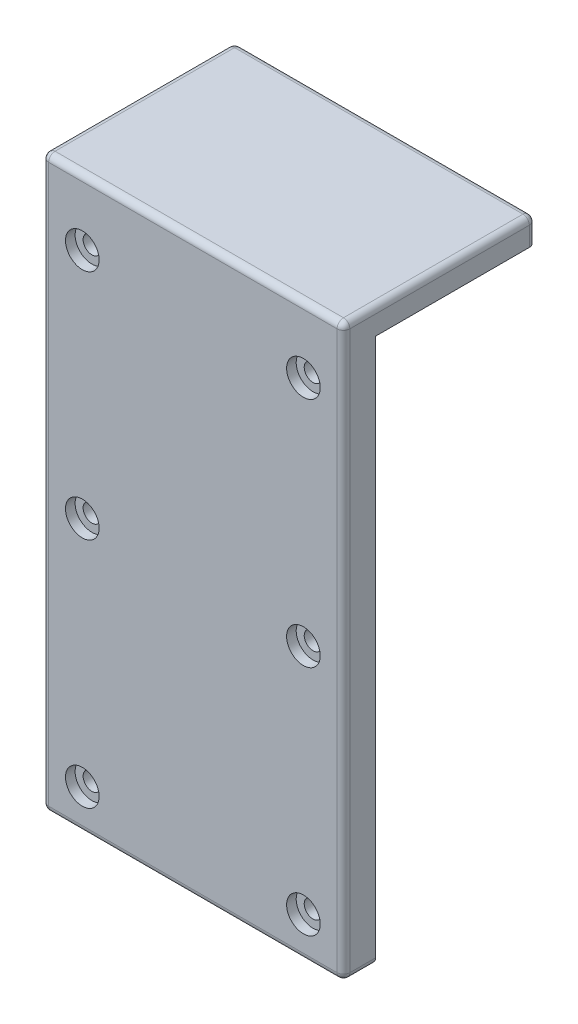
SolidWorks part; units mm, degrees
ref_plane "Front Plane" through (0, 0, 0) normal (0, 0, 1) x (1, 0, 0)
ref_plane "Top Plane" through (0, 0, 0) normal (0, 1, 0) x (1, 0, 0)
ref_plane "Right Plane" through (0, 0, 0) normal (1, 0, 0) x (0, 0, -1)
sketch "Sketch1" plane through (0, 0, 0) normal (0, 0, 1) x (1, 0, 0)
  line L1 (0, 0) -> (94, 0)
  line L2 (0, 0) -> (0, 170)
  line L3 (0, 170) -> (94, 170)
  line L4 (94, 0) -> (94, 170)
  dimension "D1" = 94
  dimension "D2" = 170
extrude "Boss-Extrude1" add sketch "Sketch1" along normal blind 10
sketch "Sketch2" plane through (0, 0, 10) normal (0, 0, 1) x (1, 0, 0)
  line L0 (12.5, 157.5) -> (12.5, 12.5) construction
  line L3 (0, 170) -> (12.5, 170) construction
  line L4 (0, 170) -> (0, 157.5) construction
  line L5 (0, 157.5) -> (12.5, 157.5) construction
  line L7 (12.5, 170) -> (12.5, 157.5) construction
  line L8 (94, 170) -> (81.5, 170) construction
  line L9 (94, 170) -> (94, 157.5) construction
  line L11 (94, 157.5) -> (81.5, 157.5) construction
  line L12 (81.5, 170) -> (81.5, 157.5) construction
  line L13 (0, 0) -> (12.5, 0) construction
  line L14 (0, 0) -> (0, 12.5) construction
  line L15 (0, 12.5) -> (12.5, 12.5) construction
  line L16 (12.5, 0) -> (12.5, 12.5) construction
  line L17 (94, 0) -> (81.5, 0) construction
  line L18 (94, 0) -> (94, 12.5) construction
  line L19 (94, 12.5) -> (81.5, 12.5) construction
  line L20 (81.5, 0) -> (81.5, 12.5) construction
  line L21 (81.5, 157.5) -> (81.5, 12.5) construction
  point P16 (12.5, 85)
  point P17 (12.5, 157.5)
  point P18 (81.5, 85)
  point P19 (12.5, 12.5)
  point P20 (81.5, 12.5)
  point P22 (81.5, 157.5)
  dimension "D1" = 69
hole_wizard "CBORE for M5 SBHCS1" positions "Sketch2" profile "Sketch3" counterbore size "M5" standard "ANSI Metric" end condition through all
sketch "Sketch3" plane through (81.5, 157.5, 10) normal (1, 0, 0) x (0, -1, 0)
  line L0 (0, 0) -> (0, 10)
  line L1 (0, 10) -> (2.75, 10)
  line L3 (2.75, 10) -> (2.75, 3)
  line L4 (2.75, 3) -> (5.25, 3)
  line L5 (5.25, 3) -> (5.25, 0)
  line L7 (5.25, 0) -> (0, 0)
  line L11 (0, -6.35) -> (0, 107.95) construction
  dimension "Thru Hole Dia." = 5.5
  dimension "Thru Hole Depth" = 10
  dimension "C'Bore Dia." = 10.5
  dimension "C'Bore Depth" = 3
sketch "Sketch4" plane through (0, 170, 0) normal (0, 1, 0) x (1, 0, 0)
  line L1 (0, -10) -> (94, -10)
  line L2 (0, -10) -> (0, 50)
  line L3 (0, 50) -> (94, 50)
  line L4 (94, -10) -> (94, 50)
  dimension "D1" = 60
extrude "Boss-Extrude2" add sketch "Sketch4" along normal blind 8
fillet "Fillet1" radius 2 11 edges at (0, 174, -50) (94, 174, -50) (47, 178, -50) (94, 0, 5) (0, 0, 5) (47, 0, 10) (0, 89, 10) (0, 178, -20) (94, 178, -20) (94, 89, 10) (47, 178, 10)
sketch "Sketch5" plane through (0, 0, 0) normal (0, 0, -1) x (-1, 0, 0)
  line L0 (0, 170) -> (0, 2) construction
  line L1 (-52.5, 150) -> (-25.5, 150)
  line L2 (-52.5, 150) -> (-52.5, 143.65)
  line L3 (-52.5, 143.65) -> (-25.5, 143.65)
  line L4 (-25.5, 150) -> (-25.5, 143.65)
  line L5 (-94, 170) -> (0, 170) construction
  line L7 (-25.5, 60.65) -> (-52.5, 60.65)
  line L8 (-25.5, 60.65) -> (-25.5, 54.3)
  line L9 (-25.5, 54.3) -> (-52.5, 54.3)
  line L10 (-52.5, 60.65) -> (-52.5, 54.3)
  dimension "D1" = 6.35
  dimension "D2" = 27
  dimension "D3" = 25.5
  dimension "D4" = 20
  dimension "D5" = 83
extrude "Boss-Extrude3" [suppressed] add sketch "Sketch5" along normal blind 10
sketch "Sketch6" [suppressed] plane through (0, 54.3, 0) normal (0, -1, 0) x (-1, 0, 0)
  line L1 (-52.5, 0) -> (-31.5, 0)
  line L2 (-52.5, 0) -> (-52.5, 3.175)
  line L3 (-52.5, 3.175) -> (-31.5, 3.175)
  line L4 (-31.5, 0) -> (-31.5, 3.175)
  dimension "D1" = 21
  dimension "D2" = 3.175
extrude "Cut-Extrude1" [suppressed] cut sketch "Sketch6" against normal up to surface (95.7 mm away) contours L3 L4 L1 L2
fillet "Fillet2" [suppressed] radius 1.5
chamfer "Chamfer1" [suppressed] distance 5 angle 78
sketch "Sketch9" plane through (0, 0, 0) normal (0, 0, -1) x (-1, 0, 0)
  line L0 (-47, 49) -> (-47, 140) construction
  line L1 (-47, 140) -> (-47, 170) construction
  line L2 (-94, 170) -> (0, 170) construction
  line L5 (-47, 140) -> (-94, 140) construction
  line L6 (-94, 2) -> (-94, 170) construction
  line L8 (-47, 140) -> (0, 140) construction
  line L9 (0, 170) -> (0, 2) construction
  point P0 (-47, 140)
  point P2 (-47, 49)
  dimension "D2" = 30
  dimension "D3" = 91
hole_wizard "M4x0.7 Tapped Hole1" positions "Sketch9" profile "Sketch10" tap size "M4x0.7" standard "ANSI Metric"
sketch "Sketch10" plane through (47, 140, 0) normal (1, 0, 0) x (0, 1, 0)
  line L0 (0, 0) -> (0, 8)
  line L1 (0, 8) -> (1.65, 8)
  line L2 (1.65, 8) -> (1.65, 0)
  line L5 (1.65, 0) -> (0, 0)
  line L10 (0, 8) -> (-1.65, 8) construction
  line L11 (0, -6.35) -> (0, 107.95) construction
  dimension "Tap Drill Dia." = 3.3
  dimension "Tap Drill Depth" = 8
  dimension "Drill Angle" = 180
cosmetic thread "Hole Thread1" parameters "D1"=8, "D2"=4
cosmetic thread "Hole Thread2" parameters "D1"=8, "D2"=4
